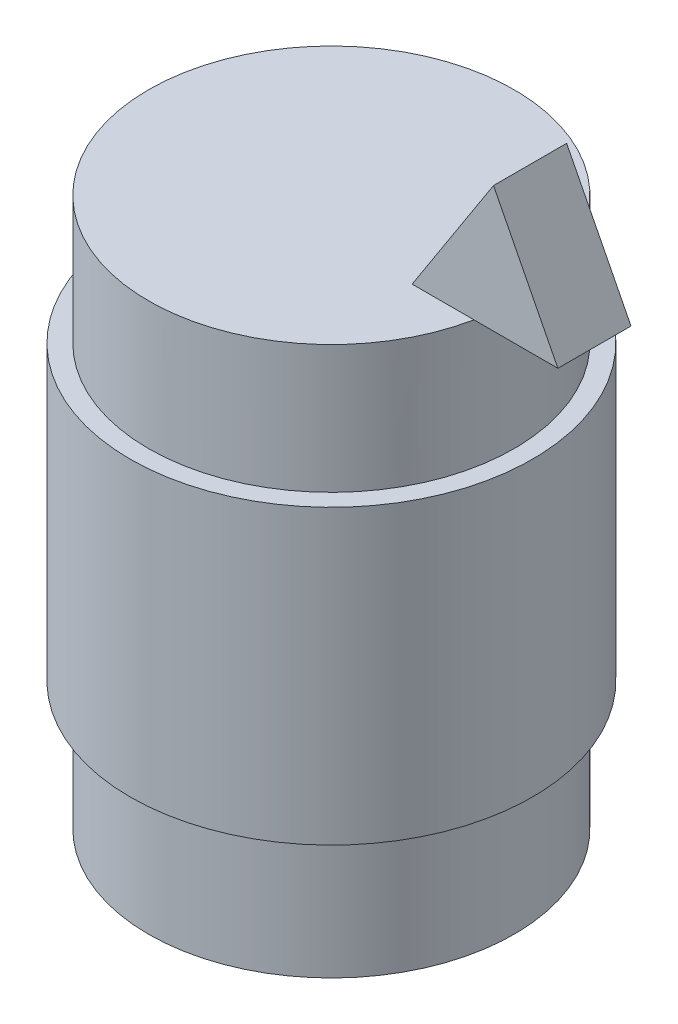
SolidWorks part; units mm, degrees
ref_plane "前视基准面" through (0, 0, 0) normal (0, 0, 1) x (1, 0, 0)
ref_plane "上视基准面" through (0, 0, 0) normal (0, 1, 0) x (1, 0, 0)
ref_plane "右视基准面" through (0, 0, 0) normal (1, 0, 0) x (0, 0, -1)
other "Configuration Table"
sketch "草图1" plane through (0, 0, 0) normal (0, 1, 0) x (1, 0, 0)
  circle A0 centre (0, 0) radius 5
extrude "凸台-拉伸1" add sketch "草图1" along normal mid plane 15
sketch "草图2" plane through (0, 0, 0) normal (0, 1, 0) x (1, 0, 0)
  circle A0 centre (0, 0) radius 5.5
extrude "凸台-拉伸2" add sketch "草图2" along normal mid plane 8
sketch "草图3" plane through (0, 0, 0) normal (0, 0, 1) x (1, 0, 0)
  line L0 (3.2088, 7.5) -> (7.1937, 7.5)
  line L1 (5, 7.5) -> (-5, 7.5) construction
  line L2 (7.1937, 7.5) -> (5.4334, 10.9477)
  line L3 (5.4334, 10.9477) -> (3.2088, 7.5)
extrude "凸台-拉伸3" add sketch "草图3" along normal mid plane 2
scale "缩放比例1" scale about centroid uniform scaling yes scale factor 3
scale "缩放比例2" scale about centroid uniform scaling yes scale factor 0.7
